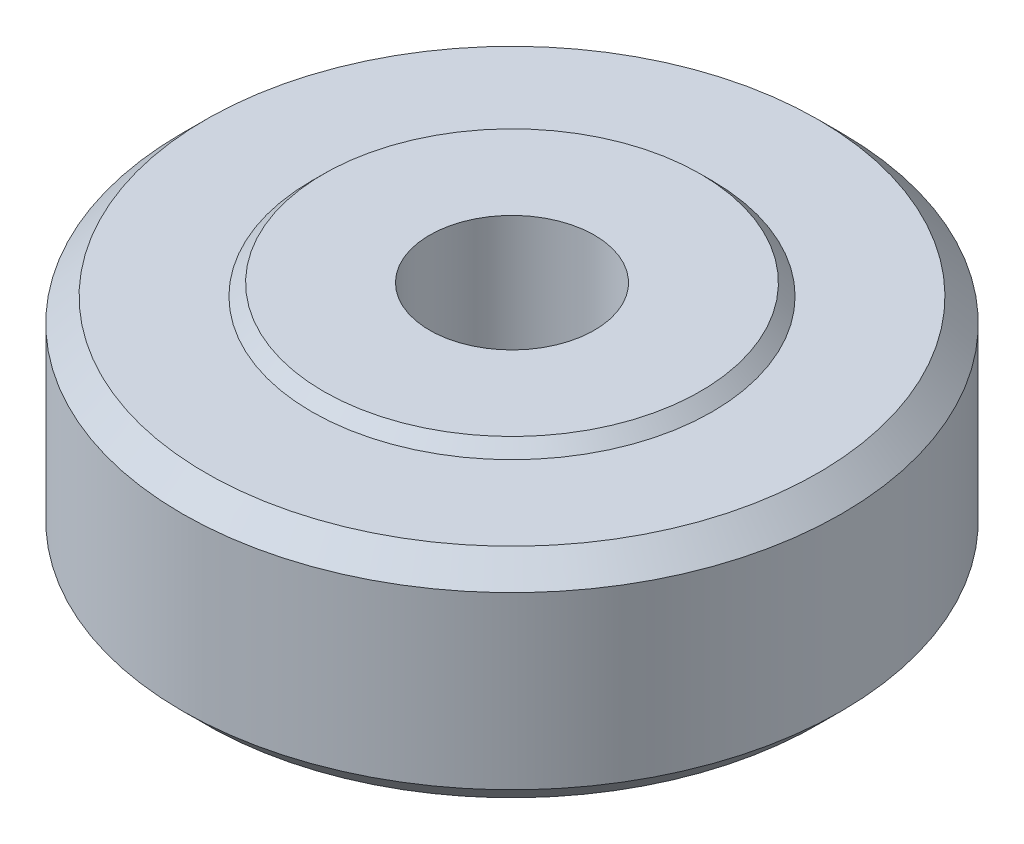
SolidWorks part; units mm, degrees
ref_plane "Plan de face" through (0, 0, 0) normal (0, 0, 1) x (1, 0, 0)
ref_plane "Plan de dessus" through (0, 0, 0) normal (0, 1, 0) x (1, 0, 0)
ref_plane "Plan de droite" through (0, 0, 0) normal (1, 0, 0) x (0, 0, -1)
sketch "Esquisse1" plane through (0, 0, 0) normal (0, 0, 1) x (1, 0, 0)
  line L0 (7, 10.25) -> (7, -10.25)
  line L1 (7, -10.25) -> (16, -10.25)
  line L2 (16, -10.25) -> (17, -9.25)
  line L3 (17, -9.25) -> (26, -9.25)
  line L4 (26, -9.25) -> (28, -7.25)
  line L5 (28, -7.25) -> (28, 7.25)
  line L6 (28, 7.25) -> (26, 9.25)
  line L7 (26, 9.25) -> (17, 9.25)
  line L8 (17, 9.25) -> (16, 10.25)
  line L9 (16, 10.25) -> (7, 10.25)
  line L10 (0, 0) -> (0, 40.2129) construction
  dimension "D1" = 20.5
  dimension "D2" = 10.25
  dimension "D3" = 16
  dimension "D4" = 7
  dimension "D5" = 18.5
  dimension "D6" = 28
  dimension "D7" = 16
  dimension "D8" = 2
  dimension "D9" = 1
  dimension "D10" = 45
  dimension "D11" = 2
revolve "Révolution1" add sketch "Esquisse1" angle 360 about L10
